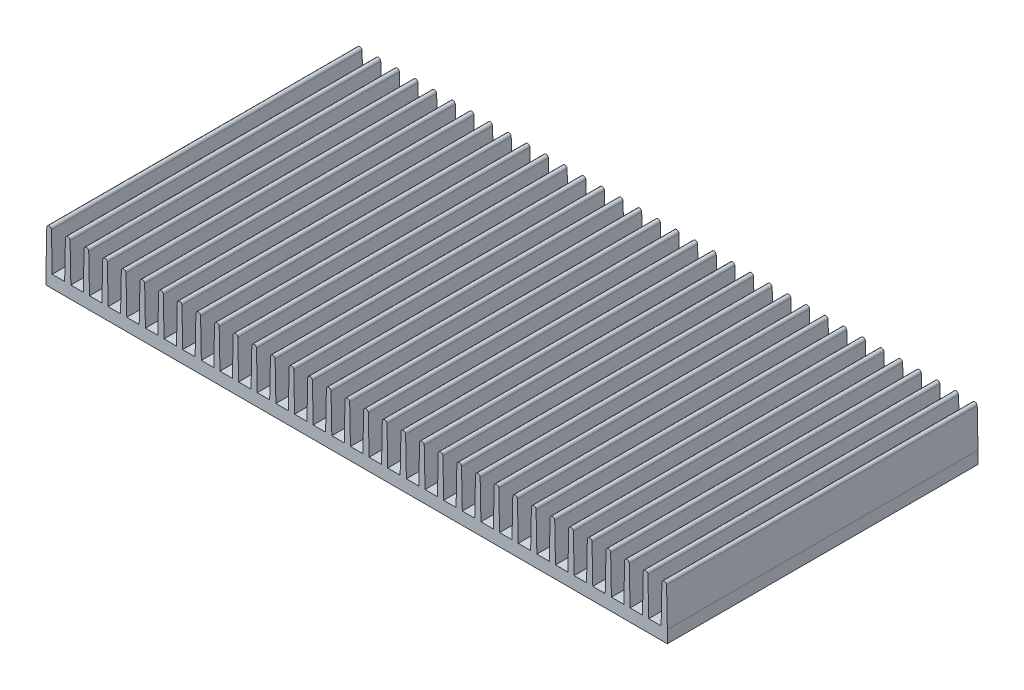
SolidWorks part; units mm, degrees
material "6061 合金"
ref_plane "正面" through (0, 0, 0) normal (0, 0, 1) x (1, 0, 0)
ref_plane "平面" through (0, 0, 0) normal (0, 1, 0) x (1, 0, 0)
ref_plane "右側面" through (0, 0, 0) normal (1, 0, 0) x (0, 0, -1)
sketch "17F200L100" plane through (0, 0, 0) normal (0, 0, 1) x (1, 0, 0)
  line L0 (-98, 4) -> (-94, 4)
  line L1 (-100, 0) -> (100, 0)
  line L2 (-93.7498, 16.2653) -> (-94, 4)
  line L3 (-99, 17) -> (100, 17) construction
  line L4 (100, 0) -> (100, 4)
  line L5 (-99, 17) -> (-99, 0) construction
  line L6 (-99.7498, 16.2653) -> (-100, 4)
  line L7 (-98.2502, 16.2653) -> (-98, 4)
  line L8 (-92.2502, 16.2653) -> (-92, 4)
  line L9 (-87.7498, 16.2653) -> (-88, 4)
  line L10 (-86.2502, 16.2653) -> (-86, 4)
  line L11 (-81.7498, 16.2653) -> (-82, 4)
  line L12 (-80.2502, 16.2653) -> (-80, 4)
  line L13 (-75.7498, 16.2653) -> (-76, 4)
  line L14 (-74.2502, 16.2653) -> (-74, 4)
  line L15 (-69.7498, 16.2653) -> (-70, 4)
  line L16 (-68.2502, 16.2653) -> (-68, 4)
  line L17 (-63.7498, 16.2653) -> (-64, 4)
  line L18 (-62.2502, 16.2653) -> (-62, 4)
  line L19 (-57.7498, 16.2653) -> (-58, 4)
  line L20 (-56.2502, 16.2653) -> (-56, 4)
  line L21 (-51.7498, 16.2653) -> (-52, 4)
  line L22 (-50.2502, 16.2653) -> (-50, 4)
  line L23 (-45.7498, 16.2653) -> (-46, 4)
  line L24 (-44.2502, 16.2653) -> (-44, 4)
  line L25 (-39.7498, 16.2653) -> (-40, 4)
  line L26 (-38.2502, 16.2653) -> (-38, 4)
  line L27 (-33.7498, 16.2653) -> (-34, 4)
  line L28 (-32.2502, 16.2653) -> (-32, 4)
  line L29 (-27.7498, 16.2653) -> (-28, 4)
  line L30 (-26.2502, 16.2653) -> (-26, 4)
  line L31 (-21.7498, 16.2653) -> (-22, 4)
  line L32 (-20.2502, 16.2653) -> (-20, 4)
  line L33 (-15.7498, 16.2653) -> (-16, 4)
  line L34 (-14.2502, 16.2653) -> (-14, 4)
  line L35 (-9.7498, 16.2653) -> (-10, 4)
  line L36 (-8.2502, 16.2653) -> (-8, 4)
  line L37 (-3.7498, 16.2653) -> (-4, 4)
  line L38 (-2.2502, 16.2653) -> (-2, 4)
  line L39 (2.2502, 16.2653) -> (2, 4)
  line L40 (3.7498, 16.2653) -> (4, 4)
  line L41 (8.2502, 16.2653) -> (8, 4)
  line L42 (9.7498, 16.2653) -> (10, 4)
  line L43 (14.2502, 16.2653) -> (14, 4)
  line L44 (15.7498, 16.2653) -> (16, 4)
  line L45 (20.2502, 16.2653) -> (20, 4)
  line L46 (21.7498, 16.2653) -> (22, 4)
  line L47 (26.2502, 16.2653) -> (26, 4)
  line L48 (27.7498, 16.2653) -> (28, 4)
  line L49 (32.2502, 16.2653) -> (32, 4)
  line L50 (33.7498, 16.2653) -> (34, 4)
  line L51 (38.2502, 16.2653) -> (38, 4)
  line L52 (39.7498, 16.2653) -> (40, 4)
  line L53 (44.2502, 16.2653) -> (44, 4)
  line L54 (45.7498, 16.2653) -> (46, 4)
  line L55 (50.2502, 16.2653) -> (50, 4)
  line L56 (51.7498, 16.2653) -> (52, 4)
  line L57 (56.2502, 16.2653) -> (56, 4)
  line L58 (57.7498, 16.2653) -> (58, 4)
  line L59 (62.2502, 16.2653) -> (62, 4)
  line L60 (63.7498, 16.2653) -> (64, 4)
  line L61 (68.2502, 16.2653) -> (68, 4)
  line L62 (69.7498, 16.2653) -> (70, 4)
  line L63 (74.2502, 16.2653) -> (74, 4)
  line L64 (75.7498, 16.2653) -> (76, 4)
  line L65 (80.2502, 16.2653) -> (80, 4)
  line L66 (81.7498, 16.2653) -> (82, 4)
  line L67 (86.2502, 16.2653) -> (86, 4)
  line L68 (87.7498, 16.2653) -> (88, 4)
  line L69 (92.2502, 16.2653) -> (92, 4)
  line L70 (93.7498, 16.2653) -> (94, 4)
  line L71 (98.2502, 16.2653) -> (98, 4)
  line L72 (99.7498, 16.2653) -> (100, 4)
  line L73 (-100, 4) -> (-100, 0)
  line L74 (100, 4) -> (100, 0)
  line L75 (-92, 4) -> (-88, 4)
  line L76 (-86, 4) -> (-82, 4)
  line L77 (-80, 4) -> (-76, 4)
  line L78 (-74, 4) -> (-70, 4)
  line L79 (-68, 4) -> (-64, 4)
  line L80 (-62, 4) -> (-58, 4)
  line L81 (-56, 4) -> (-52, 4)
  line L82 (-50, 4) -> (-46, 4)
  line L83 (-44, 4) -> (-40, 4)
  line L84 (-38, 4) -> (-34, 4)
  line L85 (-32, 4) -> (-28, 4)
  line L86 (-26, 4) -> (-22, 4)
  line L87 (-20, 4) -> (-16, 4)
  line L88 (-14, 4) -> (-10, 4)
  line L89 (-8, 4) -> (-4, 4)
  line L90 (-2, 4) -> (2, 4)
  line L91 (4, 4) -> (8, 4)
  line L92 (10, 4) -> (14, 4)
  line L93 (16, 4) -> (20, 4)
  line L94 (22, 4) -> (26, 4)
  line L95 (28, 4) -> (32, 4)
  line L96 (34, 4) -> (38, 4)
  line L97 (40, 4) -> (44, 4)
  line L98 (46, 4) -> (50, 4)
  line L99 (52, 4) -> (56, 4)
  line L100 (58, 4) -> (62, 4)
  line L101 (64, 4) -> (68, 4)
  line L102 (70, 4) -> (74, 4)
  line L103 (76, 4) -> (80, 4)
  line L104 (82, 4) -> (86, 4)
  line L105 (104.2502, 16.2653) -> (104, 4) [skipped]
  line L106 (105.7498, 16.2653) -> (106, 4) [skipped]
  line L107 (110.2502, 16.2653) -> (110, 4) [skipped]
  line L108 (111.7498, 16.2653) -> (112, 4) [skipped]
  line L109 (116.2502, 16.2653) -> (116, 4) [skipped]
  line L110 (117.7498, 16.2653) -> (118, 4) [skipped]
  line L111 (122.2502, 16.2653) -> (122, 4) [skipped]
  line L112 (123.7498, 16.2653) -> (124, 4) [skipped]
  line L113 (128.2502, 16.2653) -> (128, 4) [skipped]
  line L114 (129.7498, 16.2653) -> (130, 4) [skipped]
  line L115 (134.2502, 16.2653) -> (134, 4) [skipped]
  line L116 (135.7498, 16.2653) -> (136, 4) [skipped]
  line L117 (140.2502, 16.2653) -> (140, 4) [skipped]
  line L118 (141.7498, 16.2653) -> (142, 4) [skipped]
  line L119 (146.2502, 16.2653) -> (146, 4) [skipped]
  line L120 (147.7498, 16.2653) -> (148, 4) [skipped]
  line L121 (152.2502, 16.2653) -> (152, 4) [skipped]
  line L122 (153.7498, 16.2653) -> (154, 4) [skipped]
  line L123 (158.2502, 16.2653) -> (158, 4) [skipped]
  line L124 (159.7498, 16.2653) -> (160, 4) [skipped]
  line L125 (164.2502, 16.2653) -> (164, 4) [skipped]
  line L126 (165.7498, 16.2653) -> (166, 4) [skipped]
  line L127 (170.2502, 16.2653) -> (170, 4) [skipped]
  line L128 (171.7498, 16.2653) -> (172, 4) [skipped]
  line L129 (176.2502, 16.2653) -> (176, 4) [skipped]
  line L130 (177.7498, 16.2653) -> (178, 4) [skipped]
  line L131 (182.2502, 16.2653) -> (182, 4) [skipped]
  line L132 (183.7498, 16.2653) -> (184, 4) [skipped]
  line L133 (188.2502, 16.2653) -> (188, 4) [skipped]
  line L134 (189.7498, 16.2653) -> (190, 4) [skipped]
  line L135 (194.2502, 16.2653) -> (194, 4) [skipped]
  line L136 (195.7498, 16.2653) -> (196, 4) [skipped]
  line L137 (88, 4) -> (92, 4)
  line L138 (94, 4) -> (98, 4)
  arc A0 (-98.2502, 16.2653) -> (-99.7498, 16.2653) centre (-99, 16.25) ccw
  arc A1 (-92.2502, 16.2653) -> (-93.7498, 16.2653) centre (-93, 16.25) ccw
  arc A2 (-86.2502, 16.2653) -> (-87.7498, 16.2653) centre (-87, 16.25) ccw
  arc A3 (-80.2502, 16.2653) -> (-81.7498, 16.2653) centre (-81, 16.25) ccw
  arc A4 (-74.2502, 16.2653) -> (-75.7498, 16.2653) centre (-75, 16.25) ccw
  arc A5 (-68.2502, 16.2653) -> (-69.7498, 16.2653) centre (-69, 16.25) ccw
  arc A6 (-62.2502, 16.2653) -> (-63.7498, 16.2653) centre (-63, 16.25) ccw
  arc A7 (-56.2502, 16.2653) -> (-57.7498, 16.2653) centre (-57, 16.25) ccw
  arc A8 (-50.2502, 16.2653) -> (-51.7498, 16.2653) centre (-51, 16.25) ccw
  arc A9 (-44.2502, 16.2653) -> (-45.7498, 16.2653) centre (-45, 16.25) ccw
  arc A10 (-38.2502, 16.2653) -> (-39.7498, 16.2653) centre (-39, 16.25) ccw
  arc A11 (-32.2502, 16.2653) -> (-33.7498, 16.2653) centre (-33, 16.25) ccw
  arc A12 (-26.2502, 16.2653) -> (-27.7498, 16.2653) centre (-27, 16.25) ccw
  arc A13 (-20.2502, 16.2653) -> (-21.7498, 16.2653) centre (-21, 16.25) ccw
  arc A14 (-14.2502, 16.2653) -> (-15.7498, 16.2653) centre (-15, 16.25) ccw
  arc A15 (-8.2502, 16.2653) -> (-9.7498, 16.2653) centre (-9, 16.25) ccw
  arc A16 (-2.2502, 16.2653) -> (-3.7498, 16.2653) centre (-3, 16.25) ccw
  arc A17 (3.7498, 16.2653) -> (2.2502, 16.2653) centre (3, 16.25) ccw
  arc A18 (9.7498, 16.2653) -> (8.2502, 16.2653) centre (9, 16.25) ccw
  arc A19 (15.7498, 16.2653) -> (14.2502, 16.2653) centre (15, 16.25) ccw
  arc A20 (21.7498, 16.2653) -> (20.2502, 16.2653) centre (21, 16.25) ccw
  arc A21 (27.7498, 16.2653) -> (26.2502, 16.2653) centre (27, 16.25) ccw
  arc A22 (33.7498, 16.2653) -> (32.2502, 16.2653) centre (33, 16.25) ccw
  arc A23 (39.7498, 16.2653) -> (38.2502, 16.2653) centre (39, 16.25) ccw
  arc A24 (45.7498, 16.2653) -> (44.2502, 16.2653) centre (45, 16.25) ccw
  arc A25 (51.7498, 16.2653) -> (50.2502, 16.2653) centre (51, 16.25) ccw
  arc A26 (57.7498, 16.2653) -> (56.2502, 16.2653) centre (57, 16.25) ccw
  arc A27 (63.7498, 16.2653) -> (62.2502, 16.2653) centre (63, 16.25) ccw
  arc A28 (69.7498, 16.2653) -> (68.2502, 16.2653) centre (69, 16.25) ccw
  arc A29 (75.7498, 16.2653) -> (74.2502, 16.2653) centre (75, 16.25) ccw
  arc A30 (81.7498, 16.2653) -> (80.2502, 16.2653) centre (81, 16.25) ccw
  arc A31 (87.7498, 16.2653) -> (86.2502, 16.2653) centre (87, 16.25) ccw
  arc A32 (93.7498, 16.2653) -> (92.2502, 16.2653) centre (93, 16.25) ccw
  arc A33 (99.7498, 16.2653) -> (98.2502, 16.2653) centre (99, 16.25) ccw
  arc A50 (105.7498, 16.2653) -> (104.2502, 16.2653) centre (105, 16.25) ccw [skipped]
  arc A51 (111.7498, 16.2653) -> (110.2502, 16.2653) centre (111, 16.25) ccw [skipped]
  arc A52 (117.7498, 16.2653) -> (116.2502, 16.2653) centre (117, 16.25) ccw [skipped]
  arc A53 (123.7498, 16.2653) -> (122.2502, 16.2653) centre (123, 16.25) ccw [skipped]
  arc A54 (129.7498, 16.2653) -> (128.2502, 16.2653) centre (129, 16.25) ccw [skipped]
  arc A55 (135.7498, 16.2653) -> (134.2502, 16.2653) centre (135, 16.25) ccw [skipped]
  arc A56 (141.7498, 16.2653) -> (140.2502, 16.2653) centre (141, 16.25) ccw [skipped]
  arc A57 (147.7498, 16.2653) -> (146.2502, 16.2653) centre (147, 16.25) ccw [skipped]
  arc A58 (153.7498, 16.2653) -> (152.2502, 16.2653) centre (153, 16.25) ccw [skipped]
  arc A59 (159.7498, 16.2653) -> (158.2502, 16.2653) centre (159, 16.25) ccw [skipped]
  arc A60 (165.7498, 16.2653) -> (164.2502, 16.2653) centre (165, 16.25) ccw [skipped]
  arc A61 (171.7498, 16.2653) -> (170.2502, 16.2653) centre (171, 16.25) ccw [skipped]
  arc A62 (177.7498, 16.2653) -> (176.2502, 16.2653) centre (177, 16.25) ccw [skipped]
  arc A63 (183.7498, 16.2653) -> (182.2502, 16.2653) centre (183, 16.25) ccw [skipped]
  arc A64 (189.7498, 16.2653) -> (188.2502, 16.2653) centre (189, 16.25) ccw [skipped]
  arc A65 (195.7498, 16.2653) -> (194.2502, 16.2653) centre (195, 16.25) ccw [skipped]
  point P4 (0, 0)
  dimension "D5" = 1.5
  dimension "D1" = 4
  dimension "D2" = 50
  dimension "D3" = 17
  dimension "D4" = 200
  dimension "D6" = 1
extrude "ﾎﾞｽ - 押し出し2" add sketch "17F200L100" along normal blind 100 contours L72 A33 L71 L138 L70 A32 L69 L137 L68 A31 L67 L104 L66 A30 L65 L103 L64 A29 L63 L102 L62 A28 L61 L101 L60 A27 L59 L100 L58 A26 L57 L99 L56 A25 L55 L98 L54 A24 L53 L97 L52 A23 L51 L96 L50 A22 L49 L95 L48 A21 L47
sketch "ｽｹｯﾁ1" plane through (0, 0, 0) normal (0, -1, 0) x (1, 0, 0)
  line L0 (-84, 50) -> (81, 50) construction
  line L1 (-100, 100) -> (-100, 0) construction
  line L3 (-98, 100) -> (-94, 100) construction
  line L4 (-86, 100) -> (-82, 0) construction
  line L5 (82, 100) -> (86, 0) construction
  line L6 (-98, 100) -> (-94, 100) construction
  line L7 (-92, 100) -> (-88, 100) construction
  line L8 (-92, 100) -> (-88, 100)
  circle A0 centre (84, 50) radius 2 construction
  circle A1 centre (-84, 50) radius 2 construction
  circle A2 centre (-78, 50) radius 2
  circle A3 centre (90, 50) radius 2
  point P6 (-100, 50)
  point P13 (-84, 50)
  point P25 (-78, 50)
  point P26 (0, 0)
  point P27 (110.565, 50)
  dimension "D3" = 4
  dimension "D6" = 6
  dimension "D1" = 165
  dimension "D2" = 16
  dimension "D4" = 4
  dimension "D5" = 6
  dimension "D7" = 168
  dimension "D8" = 168
extrude "ｶｯﾄ - 押し出し1" cut sketch "ｽｹｯﾁ1" against normal through all contours A2 | A3
sketch "ｽｹｯﾁ2" plane through (0, 0, 0) normal (0, -1, 0) x (-1, 0, 0)
  circle A0 centre (48, -85) radius 2
  circle A1 centre (48, -15) radius 2
  circle A2 centre (90, -85) radius 2
  circle A3 centre (90, -15) radius 2
  dimension "D1" = 4
extrude "ｶｯﾄ - 押し出し2" cut sketch "ｽｹｯﾁ2" against normal through all
